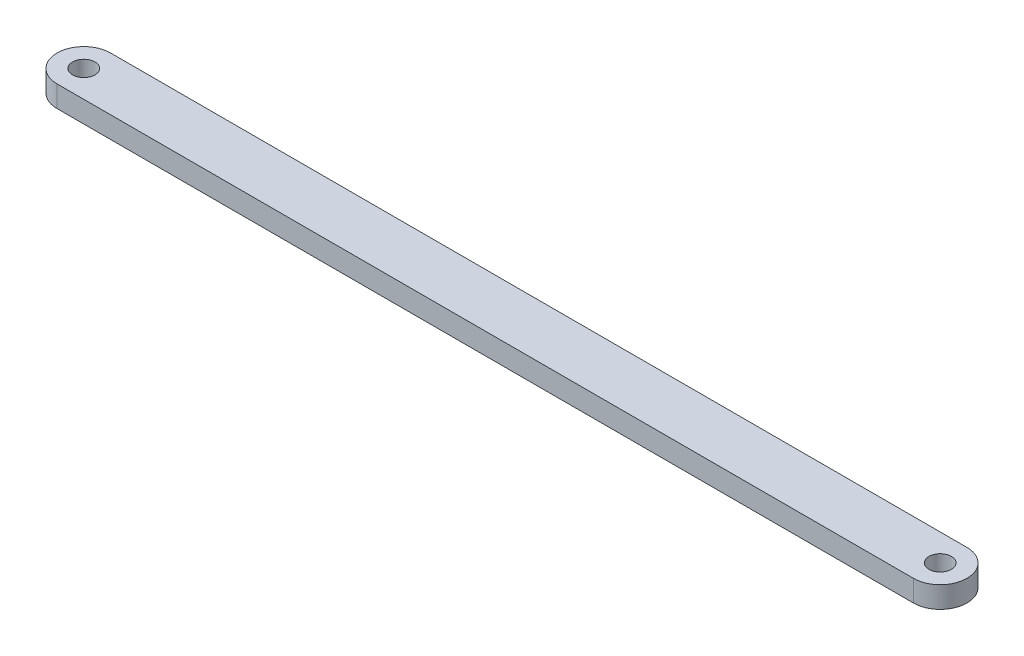
SolidWorks part; units mm, degrees
ref_plane "Front Plane" through (0, 0, 0) normal (0, 0, 1) x (1, 0, 0)
ref_plane "Top Plane" through (0, 0, 0) normal (0, 1, 0) x (1, 0, 0)
ref_plane "Right Plane" through (0, 0, 0) normal (1, 0, 0) x (0, 0, -1)
sketch "Sketch1" plane through (0, 0, 0) normal (0, 1, 0) x (1, 0, 0)
  line L0 (0, 0) -> (80, 0) construction
  line L1 (0, 2.5) -> (80, 2.5)
  line L2 (0, -2.5) -> (80, -2.5)
  arc A0 (0, 2.5) -> (0, -2.5) centre (0, 0) ccw
  arc A1 (80, -2.5) -> (80, 2.5) centre (80, 0) ccw
  circle A2 centre (0, 0) radius 1.05
  circle A3 centre (80, 0) radius 1.05
  point P3 (40, 0)
  dimension "D1" = 2.5
  dimension "D3" = 2.1
  dimension "D4" = 2.1
  dimension "D2" = 80
extrude "Boss-Extrude1" add sketch "Sketch1" along normal blind 2
